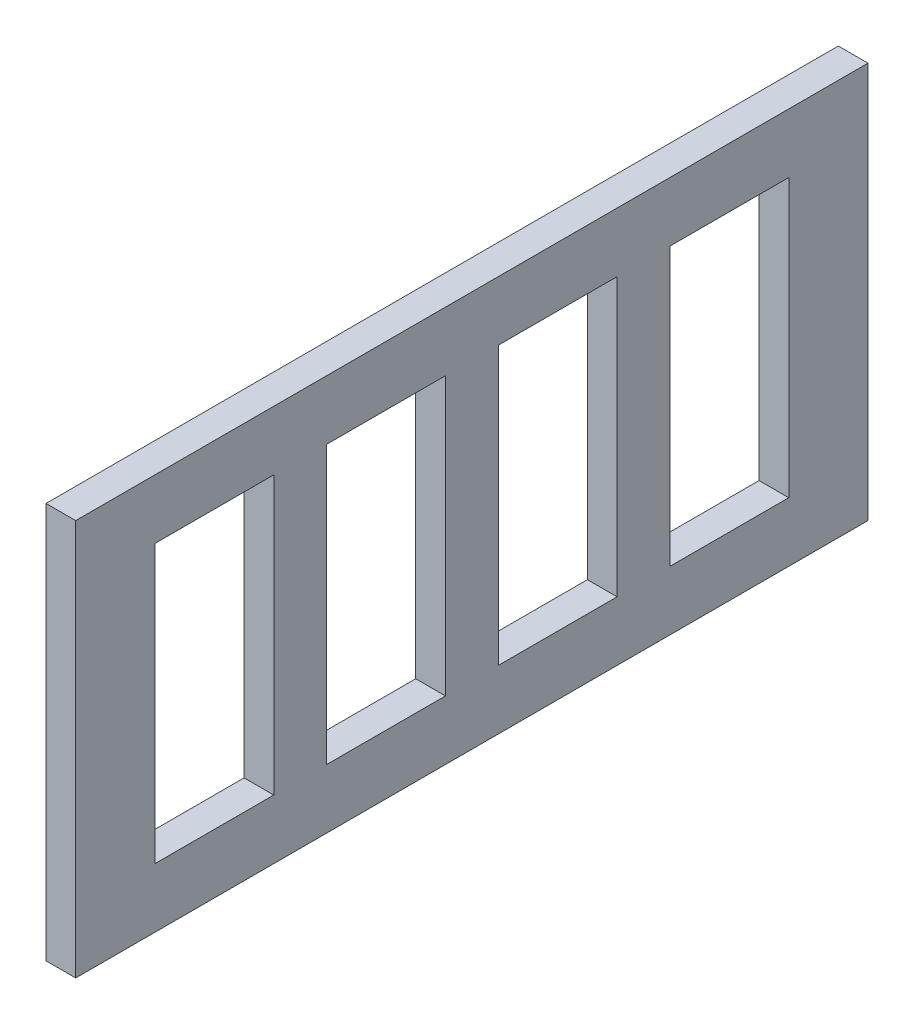
SolidWorks part; units mm, degrees
ref_plane "Front Plane" through (0, 0, 0) normal (0, 0, 1) x (1, 0, 0)
ref_plane "Top Plane" through (0, 0, 0) normal (0, 1, 0) x (1, 0, 0)
ref_plane "Right Plane" through (0, 0, 0) normal (1, 0, 0) x (0, 0, -1)
sketch "Sketch1" plane through (0, 0, 0) normal (1, 0, 0) x (0, 0, -1)
  line L1 (-200, 0) -> (200, 0)
  line L2 (-200, 0) -> (-200, 200)
  line L3 (-200, 200) -> (200, 200)
  line L4 (200, 0) -> (200, 200)
  line L5 (-160, 170) -> (-100, 170)
  line L6 (-160, 170) -> (-160, 30)
  line L7 (-160, 30) -> (-100, 30)
  line L8 (-100, 170) -> (-100, 30)
  line L52 (-160, 170) -> (-100, 170) construction
  line L109 (-73.3333, 170) -> (-73.3333, 30)
  line L110 (-73.3333, 170) -> (-13.3333, 170)
  line L111 (-13.3333, 170) -> (-13.3333, 30)
  line L112 (-73.3333, 30) -> (-13.3333, 30)
  line L113 (13.3333, 170) -> (13.3333, 30)
  line L114 (13.3333, 170) -> (73.3333, 170)
  line L115 (73.3333, 170) -> (73.3333, 30)
  line L116 (13.3333, 30) -> (73.3333, 30)
  line L117 (100, 170) -> (100, 30)
  line L118 (100, 170) -> (160, 170)
  line L119 (160, 170) -> (160, 30)
  line L120 (100, 30) -> (160, 30)
  point P4 (0, 0)
  point P10 (-130, 170)
  dimension "D1" = 400
  dimension "D2" = 200
  dimension "D3" = 30
  dimension "D4" = 30
  dimension "D5" = 40
  dimension "D6" = 60
  dimension "D8" = 40
  dimension "D7" = 4
extrude "Boss-Extrude1" add sketch "Sketch1" along normal blind 15
